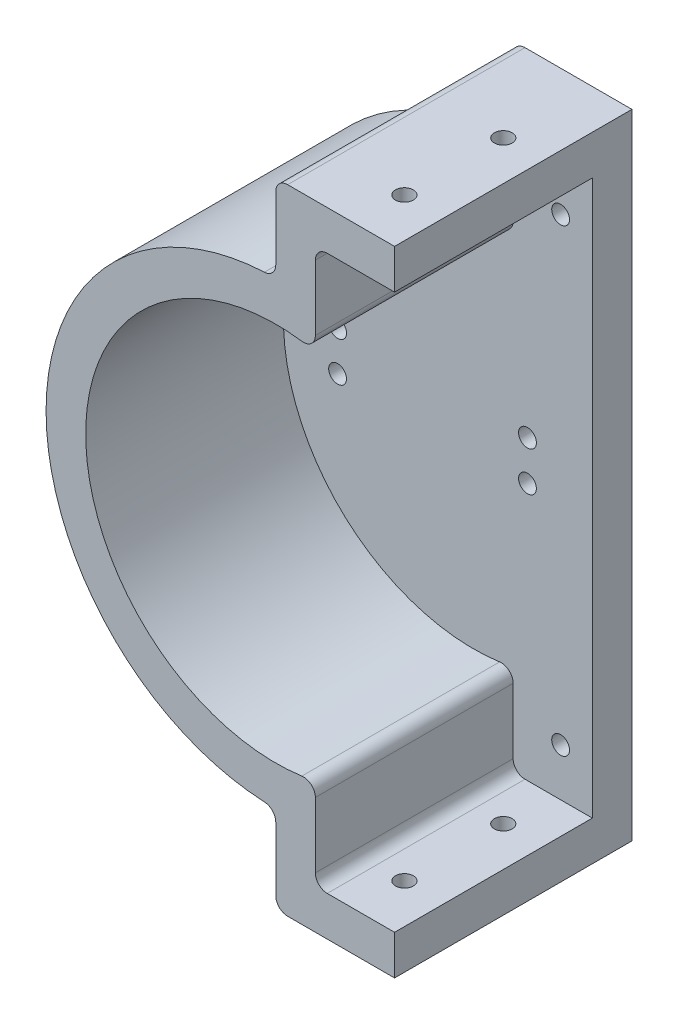
SolidWorks part; units mm, degrees
ref_plane "Front Plane" through (0, 0, 0) normal (1, 0, 0) x (0, 1, 0)
ref_plane "Top Plane" through (0, 0, 0) normal (0, 0, 1) x (0, 1, 0)
ref_plane "Right Plane" through (0, 0, 0) normal (0, 1, 0) x (-1, 0, 0)
sketch "Sketch1" plane through (0, 0, 0) normal (0, 0, 1) x (0, 1, 0)
  line L0 (0, 0) -> (0, -100) construction
  line L4 (-100.8861, 0) -> (100.8861, 0) construction
  line L12 (-58, 0) -> (-80, 0)
  line L13 (-80, 0) -> (-80, -30)
  line L14 (80, 0) -> (80, -30)
  line L15 (58, 0) -> (80, 0)
  line L16 (-80, -30) -> (80, -30)
  arc A1 (58, 0) -> (-58, 0) centre (0, 0) ccw
  dimension "D1" = 58
  dimension "D2" = 22
  dimension "D5" = 30
extrude "Boss-Extrude2" add sketch "Sketch1" along normal blind 10
sketch "Sketch3" plane through (0, 0, 10) normal (0, 0, 1) x (1, 0, 0)
  line L0 (-24.0732, 0) -> (18.5092, 0) construction
  line L1 (0, 7.3017) -> (0, -5.8366) construction
  circle A0 centre (0, 0) radius 48 construction
  circle A1 centre (13.625, -5) radius 2.25
  circle A2 centre (-34.325, -5) radius 2.25
  circle A3 centre (-34.325, 5) radius 2.25
  circle A4 centre (13.625, 5) radius 2.25
  dimension "D1" = 96
  dimension "D2" = 4.5
  dimension "D5" = 47.95
  dimension "D3" = 5
  dimension "D4" = 13.625
extrude "Cut-Extrude2" cut sketch "Sketch3" against normal through all
sketch "Sketch4" plane through (0, 0, 0) normal (0, 0, -1) x (1, 0, 0)
  circle A0 centre (-34.325, -5) radius 3.6
  circle A1 centre (-34.325, 5) radius 3.6
  circle A2 centre (13.625, 5) radius 3.6
  circle A3 centre (13.625, -5) radius 3.6
  dimension "D1" = 7.2
extrude "Cut-Extrude3" cut sketch "Sketch4" against normal blind 5
sketch "Sketch5" plane through (0, 0, 10) normal (0, 0, 1) x (1, 0, 0)
  line L0 (10, -46.9468) -> (10, -70)
  line L3 (0, 80) -> (0, 58)
  line L4 (0, 80) -> (0, 58)
  line L5 (0, -58) -> (0, -80)
  line L13 (10, -70) -> (20, -70)
  line L16 (20, 70) -> (10, 70)
  line L17 (10, 70) -> (10, 46.9468)
  line L18 (20, 70) -> (30, 70)
  line L19 (20, -70) -> (30, -70)
  line L20 (30, 70) -> (30, 80)
  line L21 (30, -80) -> (30, 80) construction
  line L24 (0, -58) -> (0, -80)
  line L25 (0, -80) -> (30, -80)
  line L26 (0, -80) -> (30, -80)
  line L27 (30, -80) -> (30, 80)
  line L28 (30, -80) -> (30, -70)
  line L29 (30, 80) -> (0, 80)
  line L30 (30, 80) -> (0, 80)
  line L33 (20, -70) -> (20, 70) construction
  arc A1 (0, 58) -> (0, -58) centre (0, 0) ccw
  arc A2 (0, 58) -> (0, -58) centre (0, 0) ccw
  arc A3 (10, 46.9468) -> (10, -46.9468) centre (0, 0) ccw
  dimension "D2" = 10
  dimension "D1" = 0
extrude "Boss-Extrude4" add sketch "Sketch5" along normal blind 49.94
sketch "Sketch7" plane through (0, -70, 0) normal (0, 1, 0) x (-1, 0, 0)
  line L0 (-30, 34.97) -> (8.3655, 34.97) construction
  line L1 (-30, 59.94) -> (-30, 10) construction
  circle A0 centre (-20, 47.455) radius 2.25
  circle A1 centre (-20, 22.485) radius 2.25
  point P6 (0, 0)
  dimension "D2" = 4.5
  dimension "D1" = 12.485
  dimension "D3" = 10
extrude "Cut-Extrude5" cut sketch "Sketch7" against normal through all both and the other way through all
sketch "Sketch8" plane through (0, 0, 10) normal (0, 0, 1) x (1, 0, 0)
  line L0 (10, -70) -> (10, -46.9468) construction
  line L2 (30, -70) -> (10, -70) construction
  line L3 (32.967, 0) -> (-32.967, 0) construction
  circle A0 centre (22, -58) radius 2.25
  circle A1 centre (22, 58) radius 2.25
  point P2 (0, 0)
  point P5 (0, 0)
  point P7 (-37.4245, -58.396)
  dimension "D1" = 4.5
  dimension "D2" = 12
  dimension "D3" = 12
extrude "Cut-Extrude6" cut sketch "Sketch8" against normal through all both and the other way through all
fillet "Fillet1" radius 3 8 edges at (0, 58, 29.97) (0, 80, 29.97) (10, 70, 34.97) (10, 46.9468, 34.97) (10, -46.9468, 34.97) (0, -58, 29.97) (0, -80, 29.97) (10, -70, 34.97)
sketch "Sketch9" plane through (0, 0, 0) normal (0, 0, -1) x (1, 0, 0)
  line L0 (-32.967, 0) -> (32.967, 0) construction
  circle A0 centre (22, 58) radius 3.6
  circle A1 centre (22, -58) radius 3.6
  dimension "D1" = 7.2
extrude "Cut-Extrude7" cut sketch "Sketch9" against normal blind 5 and the other way through all
